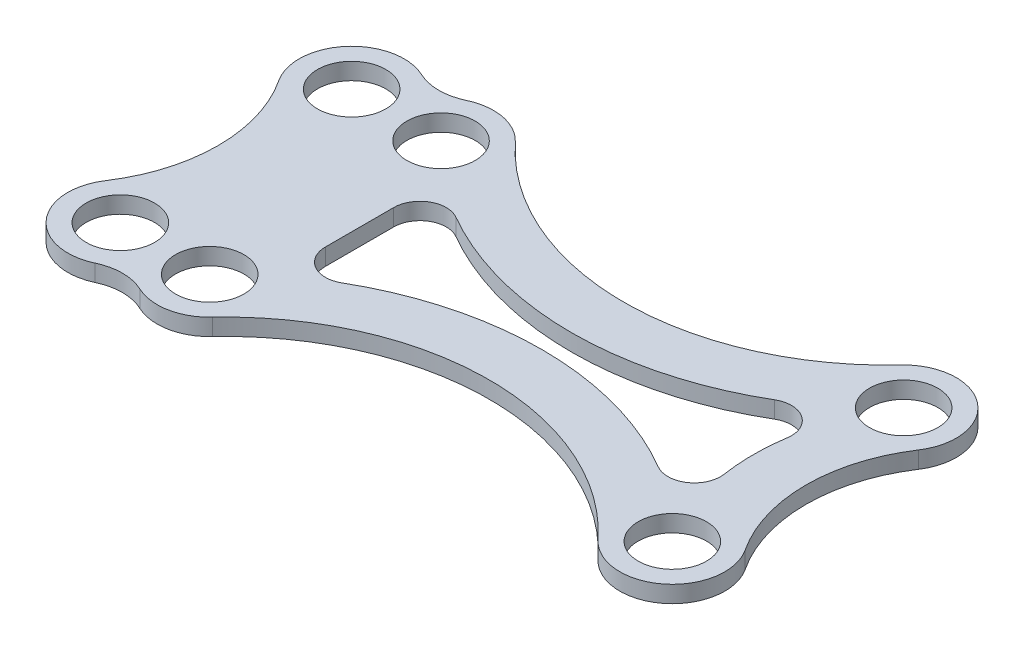
SolidWorks part; units mm, degrees
ref_plane "Front Plane" through (0, 0, 0) normal (0, 0, 1) x (1, 0, 0)
ref_plane "Top Plane" through (0, 0, 0) normal (0, 1, 0) x (1, 0, 0)
ref_plane "Right Plane" through (0, 0, 0) normal (1, 0, 0) x (0, 0, -1)
sketch "Sketch1" plane through (0, 0, 0) normal (0, 1, 0) x (1, 0, 0)
  line L0 (-15.8063, 0) -> (129.3245, 0) construction
  line L1 (0, 50.1132) -> (0, -46.1616) construction
  line L2 (17, 50.1132) -> (17, -46.1616) construction
  line L3 (105, 50.1132) -> (105, -46.1616) construction
  line L4 (129.3245, 22) -> (-15.8063, 22) construction
  arc A0 (4.25, 31.0519) -> (-8.3516, 16.5) centre (0, 22) ccw
  arc A2 (113.3516, 16.5) -> (97.6667, 28.7987) centre (105, 22) ccw
  arc A3 (113.3516, -16.5) -> (97.6667, -28.7987) centre (105, -22) cw
  arc A4 (24.3333, -28.7987) -> (12.75, -31.0519) centre (17, -22) cw
  arc A5 (4.25, -31.0519) -> (-8.3516, -16.5) centre (0, -22) cw
  arc A6 (4.25, 31.0519) -> (12.75, 31.0519) centre (8.5, 40.1039) ccw
  arc A7 (24.3333, 28.7987) -> (97.6667, 28.7987) centre (61, 62.7922) ccw
  arc A8 (113.3516, 16.5) -> (113.3516, -16.5) centre (138.4066, 0) ccw
  arc A9 (-8.3516, 16.5) -> (-8.3516, -16.5) centre (-33.4066, 0) cw
  arc A10 (24.3333, -28.7987) -> (97.6667, -28.7987) centre (61, -62.7922) cw
  arc A11 (4.25, -31.0519) -> (12.75, -31.0519) centre (8.5, -40.1039) cw
  arc A12 (24.3333, 28.7987) -> (12.75, 31.0519) centre (17, 22) ccw
  point P12 (0, 0)
  dimension "D4" = 20
  dimension "D5" = 20
  dimension "D6" = 50
  dimension "D7" = 30
  dimension "D8" = 30
  dimension "D9" = 10
  dimension "D10" = 10
  dimension "D1" = 22
  dimension "D2" = 88
  dimension "D3" = 105
extrude "base" add sketch "Sketch1" against normal blind 3.2
sketch "Sketch2" plane through (0, 0, 0) normal (0, 1, 0) x (1, 0, 0)
  circle A0 centre (0, 22) radius 6.5
  circle A1 centre (17, 22) radius 6.5
  circle A2 centre (105, 22) radius 6.5
  circle A3 centre (105, -22) radius 6.5
  circle A4 centre (17, -22) radius 6.5
  circle A5 centre (0, -22) radius 6.5
  arc A6 (4.25, 31.0519) -> (-8.3516, 16.5) centre (0, 22) ccw construction
  arc A7 (24.3333, 28.7987) -> (12.75, 31.0519) centre (17, 22) ccw construction
  arc A8 (-8.3516, -16.5) -> (4.25, -31.0519) centre (0, -22) ccw construction
  arc A9 (12.75, -31.0519) -> (24.3333, -28.7987) centre (17, -22) ccw construction
  arc A10 (97.6667, -28.7987) -> (113.3516, -16.5) centre (105, -22) ccw construction
  arc A11 (113.3516, 16.5) -> (97.6667, 28.7987) centre (105, 22) ccw construction
  dimension "D1" = 13
extrude "holes" cut sketch "Sketch2" against normal through all
sketch "Sketch3" plane through (0, 0, 0) normal (0, 1, 0) x (-1, 0, 0)
  line L0 (-23.5, -6.5005) -> (-23.5, 6.5005)
  arc A3 (-31, -10.8306) -> (-23.5, -6.5005) centre (-28.5, -6.5005) ccw
  arc A4 (-23.5, 6.5005) -> (-31, 10.8306) centre (-28.5, 6.5005) ccw
  circle A5 centre (-17, -22) radius 6.5 construction
  arc A6 (-91.3826, 11.0534) -> (-98.858, 5.9928) centre (-93.9145, 6.7418) ccw
  arc A7 (-91.3826, -11.0534) -> (-98.858, -5.9928) centre (-93.9145, -6.7418) cw
  arc A25 (-24.3333, -28.7987) -> (-97.6667, -28.7987) centre (-61, -62.7922) ccw construction
  arc A26 (-97.6667, 28.7987) -> (-24.3333, 28.7987) centre (-61, 62.7922) ccw construction
  arc A27 (-113.3516, -16.5) -> (-113.3516, 16.5) centre (-138.4066, 0) ccw construction
  arc A44 (-91.3826, 11.0534) -> (-31, 10.8306) centre (-61, 62.7922) ccw
  arc A45 (-98.858, -5.9928) -> (-98.858, 5.9928) centre (-138.4066, 0) ccw
  arc A46 (-31, -10.8306) -> (-91.3826, -11.0534) centre (-61, -62.7922) ccw
  dimension "D2" = 60
  dimension "D3" = 40
  dimension "D1" = 5
  dimension "D5" = 60
  dimension "D7" = 5
extrude "cutaway" cut sketch "Sketch3" against normal through all
